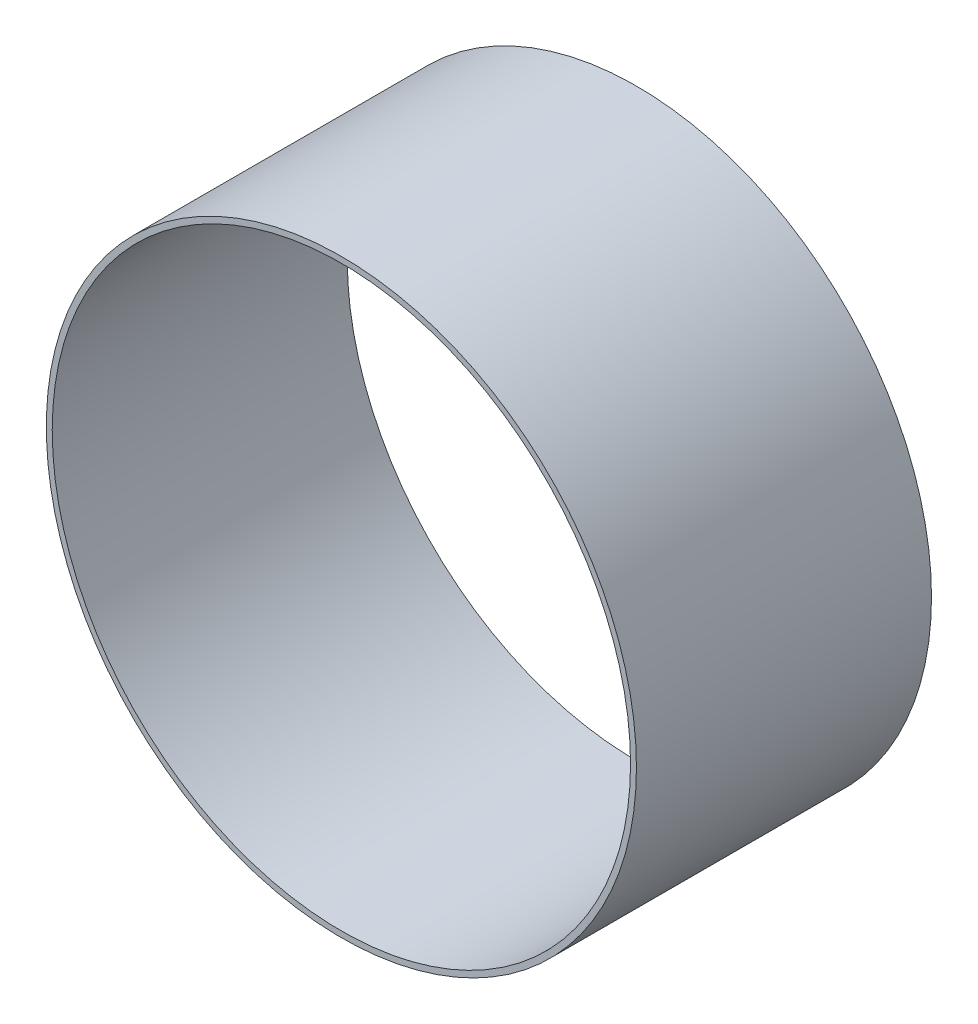
SolidWorks part; units mm, degrees
ref_plane "Plan de face" through (0, 0, 0) normal (0, 0, 1) x (1, 0, 0)
ref_plane "Plan de dessus" through (0, 0, 0) normal (0, 1, 0) x (1, 0, 0)
ref_plane "Plan de droite" through (0, 0, 0) normal (1, 0, 0) x (0, 0, -1)
sketch "Esquisse1" plane through (0, 0, 0) normal (0, 0, 1) x (1, 0, 0)
  circle A0 centre (0, 0) radius 50
  circle A1 centre (0, 0) radius 49
  dimension "D1" = 100
  dimension "D2" = 98
extrude "Boss.-Extru.1" add sketch "Esquisse1" along normal blind 50
